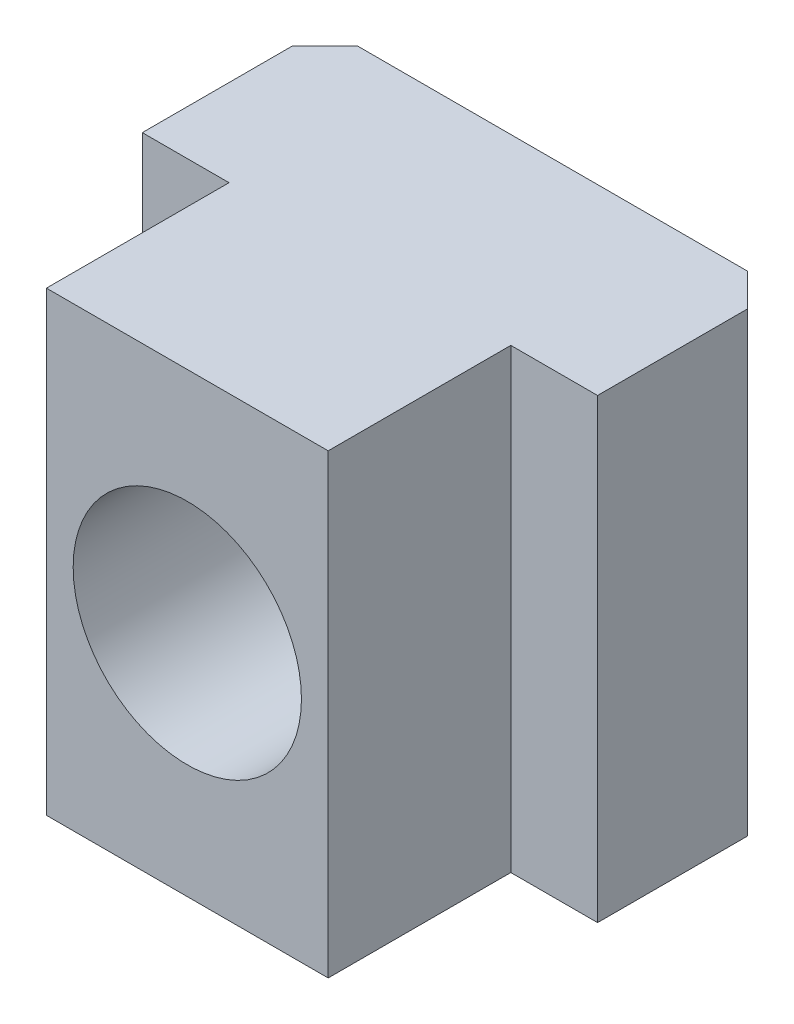
SolidWorks part; units mm, degrees
material "1.0553 (S355J0)"
ref_plane "XY Plane" through (0, 0, 0) normal (0, 0, 1) x (1, 0, 0)
ref_plane "XZ Plane" through (0, 0, 0) normal (0, 1, 0) x (1, 0, 0)
ref_plane "YZ Plane" through (0, 0, 0) normal (1, 0, 0) x (0, 0, -1)
sketch "Sketch1" plane through (0, 0, 0) normal (0, 1, 0) x (1, 0, 0)
  line L0 (-10.8, 0) -> (-17.45, 0)
  line L1 (-17.45, 0) -> (-17.45, 11.5)
  line L2 (-14.95, 14) -> (14.95, 14)
  line L3 (17.45, 11.5) -> (17.45, 0)
  line L4 (17.45, 0) -> (10.8, 0)
  line L5 (10.8, 0) -> (10.8, -14)
  line L6 (10.8, -14) -> (-10.8, -14)
  line L7 (-10.8, -14) -> (-10.8, 0)
  line L8 (0, -22.8019) -> (0, 20.8028) construction
  line L9 (-10.8, 0) -> (10.8, 0) construction
  line L10 (-17.45, 11.5) -> (-14.95, 14)
  line L11 (14.95, 14) -> (17.45, 11.5)
  point P4 (-17.45, 14)
  point P5 (17.45, 14)
  dimension "D1" = 14
  dimension "D2" = 28
  dimension "D3" = 21.6
  dimension "D4" = 34.9
extrude "Boss-Extrude1" add sketch "Sketch1" along normal mid plane 35
hole_wizard "M20 Tapped Hole1" positions "Sketch2" profile "Sketch3" tap size "M20" standard "ISO" end condition through all
sketch "Sketch2" plane through (0, 0, 14) normal (0, 0, 1) x (1, 0, 0)
  point P0 (0, 0)
sketch "Sketch3" plane through (0, 0, 14) normal (1, 0, 0) x (0, -1, 0)
  line L0 (0, 0) -> (0, 28)
  line L1 (0, 28) -> (8.75, 28)
  line L2 (8.75, 28) -> (8.75, 0)
  line L5 (8.75, 0) -> (0, 0)
  line L11 (0, -6.35) -> (0, 107.95) construction
  dimension "Thru Tap Drill Dia." = 17.5
  dimension "Thru Tap Drill Depth" = 28
cosmetic thread "Hole Thread1"
sketch "Sketch4" [suppressed] plane through (0, 0, 14) normal (0, 0, 1) x (1, 0, 0)
  line L0 (-17.45, 5.0886) -> (18.8816, 18.3122)
  line L1 (0, 0) -> (0, 17.5) construction
  line L2 (-10.8, 17.5) -> (10.8, 17.5) construction
  line L6 (-17.45, 17.5) -> (-17.45, -17.5) construction
  line L9 (-17.45, 18.3122) -> (-17.45, 5.0886)
  line L10 (-17.45, 18.3122) -> (18.8816, 18.3122)
  circle A0 centre (0, 0) radius 10.75 construction
  dimension "D2" = 21.5
  dimension "D1" = 70
extrude "Cut-Extrude1" [suppressed] cut sketch "Sketch4" against normal through all contours L0 L10 L9
pattern_circular "CirPattern1" [suppressed] count 2 every 180
fillet "Fillet1" [suppressed] radius 10
